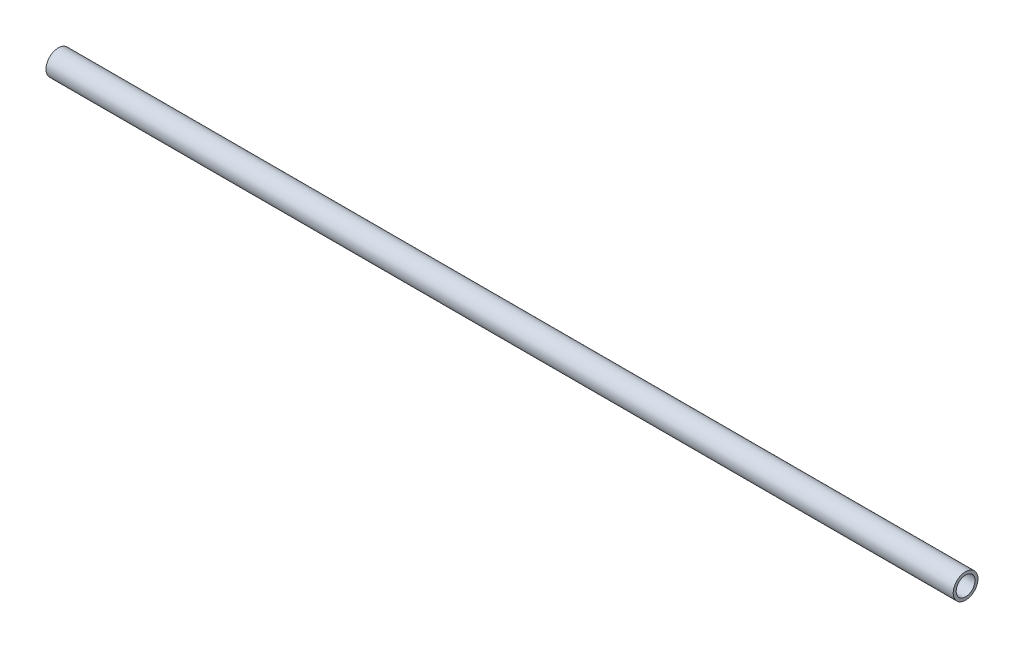
SolidWorks part; units mm, degrees
material "AISI 4130 Steel, annealed at 865C"
ref_plane "Front Plane" through (0, 0, 0) normal (0, 0, 1) x (1, 0, 0)
ref_plane "Top Plane" through (0, 0, 0) normal (0, 1, 0) x (1, 0, 0)
ref_plane "Right Plane" through (0, 0, 0) normal (1, 0, 0) x (0, 0, -1)
sketch "Sketch1" plane through (0, 0, 0) normal (1, 0, 0) x (0, 0, -1)
  circle A0 centre (0, 0) radius 12.7
  circle A1 centre (0, 0) radius 9.652
  dimension "D1" = 25.4
  dimension "D2" = 19.304
extrude "Boss-Extrude1" add sketch "Sketch1" along normal blind 930
